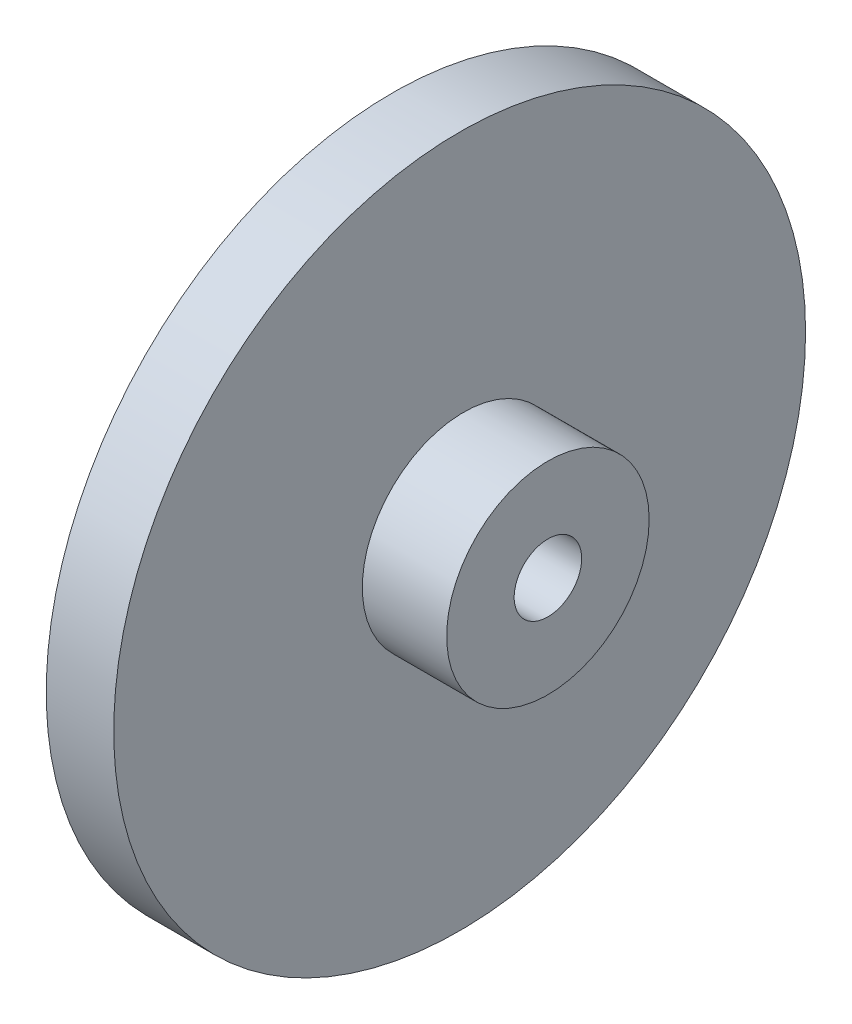
SolidWorks part; units mm, degrees
material "AISI 1035 Steel (SS)"
ref_plane "Front" through (0, 0, 0) normal (0, 0, 1) x (1, 0, 0)
ref_plane "Top" through (0, 0, 0) normal (0, 1, 0) x (1, 0, 0)
ref_plane "Right" through (0, 0, 0) normal (1, 0, 0) x (0, 0, -1)
sketch "Sketch1" plane through (0, 0, 0) normal (1, 0, 0) x (0, 0, -1)
  circle A0 centre (0, -0.1972) radius 20.5
  circle A1 centre (0.2308, -0.1972) radius 2
  dimension "D1" = 41
  dimension "D2" = 4
extrude "Boss-Extrude1" add sketch "Sketch1" along normal blind 4
sketch "Sketch2" plane through (4, 0, 0) normal (1, 0, 0) x (0, 0, -1)
  circle A0 centre (0.2308, -0.1972) radius 6
  circle A2 centre (0.2308, -0.1972) radius 2
  dimension "D1" = 12
extrude "Boss-Extrude3" add sketch "Sketch2" along normal blind 5
